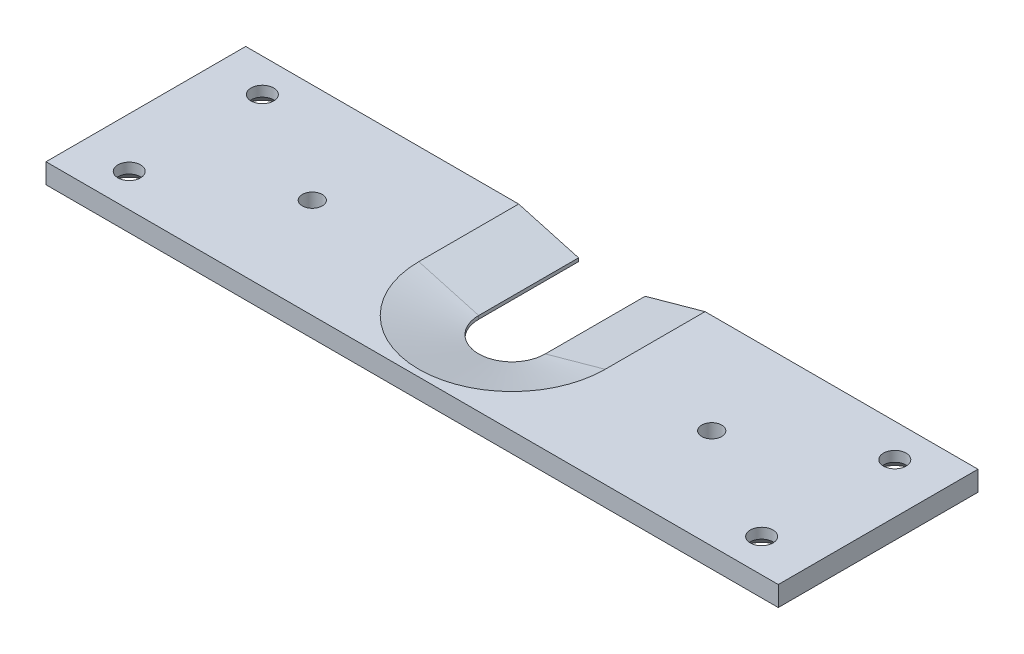
SolidWorks part; units mm, degrees
ref_plane "Front Plane" through (0, 0, 0) normal (0, 0, 1) x (1, 0, 0)
ref_plane "Top Plane" through (0, 0, 0) normal (0, 1, 0) x (1, 0, 0)
ref_plane "Right Plane" through (0, 0, 0) normal (1, 0, 0) x (0, 0, -1)
sketch "Sketch1" plane through (0, 0, 0) normal (0, 1, 0) x (1, 0, 0)
  line L1 (-55, 15) -> (55, 15)
  line L2 (-55, 15) -> (-55, -15)
  line L3 (-55, -15) -> (55, -15)
  line L4 (55, 15) -> (55, -15)
  dimension "D1" = 55
  dimension "D2" = 55
  dimension "D4" = 15
  dimension "D5" = 15
extrude "Extrude1" add sketch "Sketch1" along normal blind 3
sketch "Sketch2" plane through (0, 3, 0) normal (0, 1, 0) x (-1, 0, 0)
  line L0 (-55, -15) -> (55, -15) construction
  line L2 (5, 0) -> (5, -15)
  line L3 (5, -15) -> (-5, -15)
  line L4 (-5, 0) -> (-5, -15)
  arc A1 (5, 0) -> (-5, 0) centre (0, 0) ccw
extrude "Cut-Extrude1" cut sketch "Sketch2" against normal through all
chamfer "Chamfer1" distance 9 distance2 2.5 3 edges at (5, 3, -7.5) (0, 3, 5) (-5, 3, -7.5)
hole_wizard "CSK for M3 Countersunk Raised Head Screw1" positions "Sketch9" profile "Sketch8" countersink size "M3" standard "ISO" end condition through all
sketch "Sketch9" plane through (0, 0, 0) normal (0, -1, 0) x (1, 0, 0)
  line L0 (-55, -15) -> (-55, 15) construction
  line L1 (55, 15) -> (55, -15) construction
  line L3 (-55, 15) -> (55, 15) construction
  line L4 (55, -15) -> (5, -15) construction
  point P0 (47.5, -10)
  point P1 (-47.5, -10)
  point P4 (-47.5, 10)
  point P6 (47.5, 10)
  dimension "D1" = 7.5
  dimension "D2" = 7.5
  dimension "D3" = 5
  dimension "D4" = 5
sketch "Sketch8" plane through (47.5, 0, -10) normal (1, 0, 0) x (0, 0, -1)
  line L0 (0, 0) -> (0, 3)
  line L1 (0, 3) -> (1.7, 3)
  line L2 (1.7, 3) -> (1.7, 1.45)
  line L3 (1.7, 1.45) -> (3.15, 0)
  line L5 (3.15, 0) -> (0, 0)
  line L6 (-1.7, 1.45) -> (-3.15, 0) construction
  line L11 (0, -6.35) -> (0, 107.95) construction
  dimension "Thru Hole Dia." = 3.4
  dimension "Thru Hole Depth" = 3
  dimension "Near C'Sink Dia." = 6.3
  dimension "Near C'Sink Angle" = 90
hole_wizard "M3 Tapped Hole1" positions "Sketch11" profile "Sketch12" tap size "M3" standard "ISO" end condition through all
sketch "Sketch11" plane through (0, 3, 0) normal (0, 1, 0) x (-1, 0, 0)
  line L0 (55, 15) -> (-55, 15) construction
  line L1 (-55, 15) -> (-55, -15) construction
  line L2 (55, -15) -> (55, 15) construction
  point P5 (-30, 0)
  point P7 (30, 0)
  dimension "D1" = 15
  dimension "D2" = 25
  dimension "D3" = 25
sketch "Sketch12" plane through (30, 3, 0) normal (1, 0, 0) x (0, 0, 1)
  line L0 (0, 0) -> (0, 3)
  line L1 (0, 3) -> (1.5, 3)
  line L2 (1.5, 3) -> (1.5, 0)
  line L5 (1.5, 0) -> (0, 0)
  line L11 (0, -6.35) -> (0, 107.95) construction
  dimension "Thread Major Dia." = 3
  dimension "Thru Tap Drill Depth" = 3
sketch "Sketch13" plane through (0, 0, 0) normal (0, -1, 0) x (1, 0, 0)
  circle A0 centre (0, -32.271) radius 30.9632
equation "\"D2@Sketch1\" = \"D1@Sketch1\""
equation "\"D5@Sketch1\"=\"D4@Sketch1\""
equation "\"D2@Sketch9\" = \"D1@Sketch9\""
equation "\"D4@Sketch9\" = \"D3@Sketch9\""
equation "\"D3@Sketch11\" = \"D2@Sketch11\""
